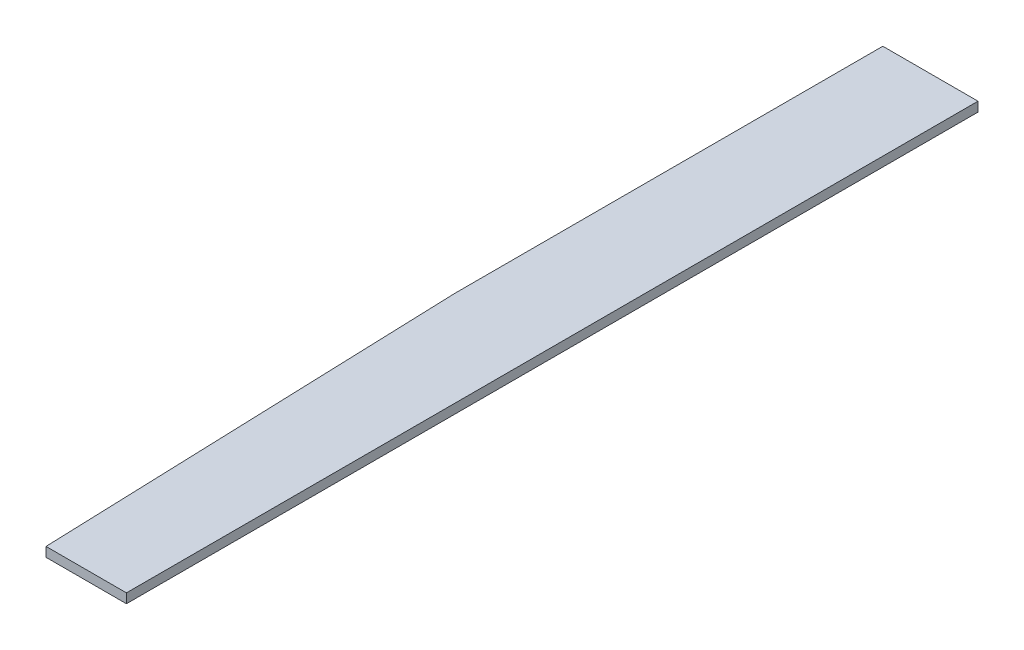
SolidWorks part; units mm, degrees
ref_plane "Front Plane" through (0, 0, 0) normal (0, 0, 1) x (1, 0, 0)
ref_plane "Top Plane" through (0, 0, 0) normal (0, 1, 0) x (1, 0, 0)
ref_plane "Right Plane" through (0, 0, 0) normal (1, 0, 0) x (0, 0, -1)
sketch "Sketch1" plane through (0, 0, 0) normal (0, 1, 0) x (1, 0, 0)
  line L0 (0, 0) -> (-42.5, 0)
  line L1 (0, 0) -> (0, 450)
  line L2 (-50.3, 450) -> (0, 450)
  line L3 (-50.3, 450) -> (-50.3, 223.7821)
  line L4 (-50.3, 223.7821) -> (-42.5, 0)
  point P4 (-50.3, 228.369)
  point P6 (-50.3, 223.6444)
  dimension "D1" = 42.5
  dimension "D2" = 50.3
  dimension "D3" = 450
extrude "Boss-Extrude1" add sketch "Sketch1" along normal blind 5
